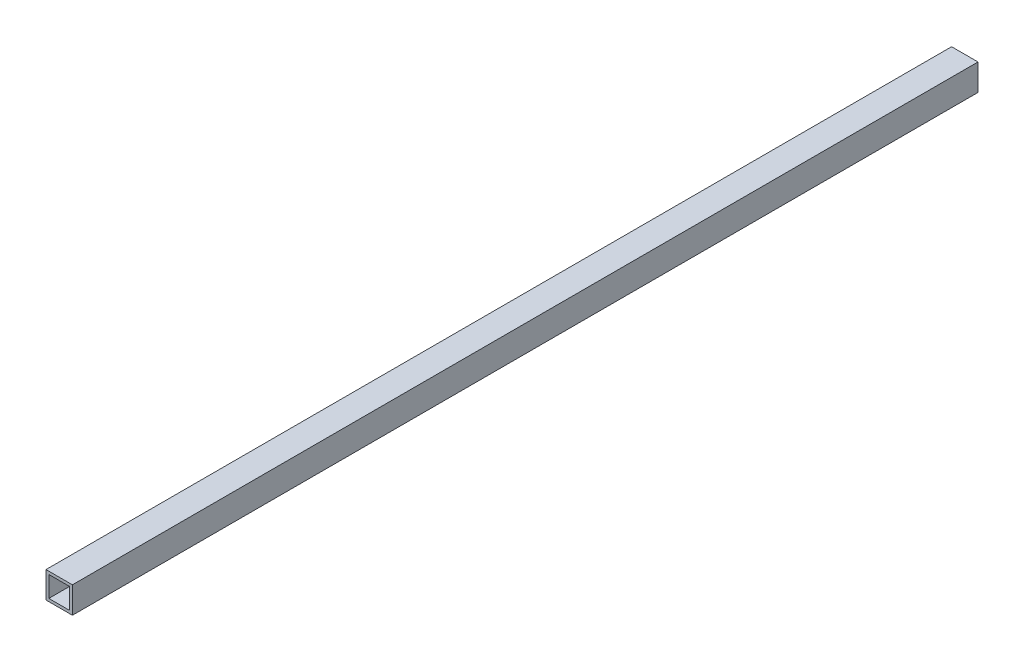
SolidWorks part; units mm, degrees
ref_plane "前视基准面" through (0, 0, 0) normal (0, 0, 1) x (1, 0, 0)
ref_plane "上视基准面" through (0, 0, 0) normal (0, 1, 0) x (1, 0, 0)
ref_plane "右视基准面" through (0, 0, 0) normal (1, 0, 0) x (0, 0, -1)
sketch "草图1" plane through (0, 0, 0) normal (0, 0, 1) x (1, 0, 0)
  line L1 (-5.5, 5.5) -> (5.5, 5.5)
  line L2 (-5.5, 5.5) -> (-5.5, -5.5)
  line L3 (-5.5, -5.5) -> (5.5, -5.5)
  line L4 (5.5, 5.5) -> (5.5, -5.5)
  line L5 (-5.5, 5.5) -> (5.5, -5.5) construction
  line L6 (-5.5, -5.5) -> (5.5, 5.5) construction
  point P0 (0, 0)
  dimension "D1" = 11
extrude "拉伸-薄壁1" add sketch "草图1" along normal blind 480 thin thin type one direction wall 1.5
